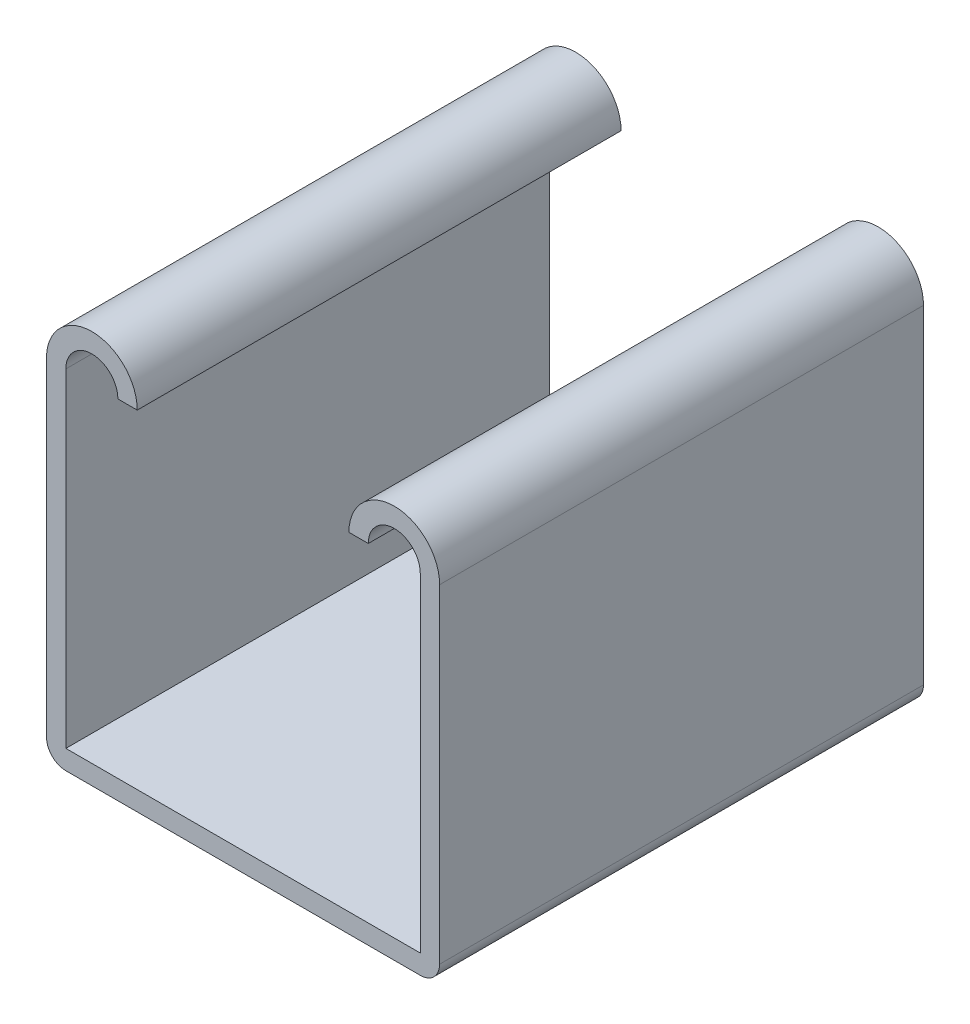
SolidWorks part; units mm, degrees
ref_plane "Plane1" through (0, 0, 0) normal (0, 0, 1) x (1, 0, 0)
ref_plane "Plane2" through (0, 0, 0) normal (0, 1, 0) x (1, 0, 0)
ref_plane "Plane3" through (0, 0, 0) normal (1, 0, 0) x (0, 0, -1)
sketch "Sketch1" plane through (0, 0, 0) normal (0, 0, 1) x (1, 0, 0)
  line L0 (-10.3188, 9.3789) -> (-10.3187, -7.874)
  line L1 (-9.3027, -8.89) -> (9.3028, -8.89)
  line L2 (10.3187, -7.874) -> (10.3187, 9.3789)
  line L3 (-6.5723, 9.3789) -> (-5.5562, 9.3789)
  line L4 (5.5562, 9.3789) -> (6.5722, 9.3789)
  line L6 (-9.3027, 9.3789) -> (-9.3027, -7.874)
  line L7 (-9.3027, -7.874) -> (9.3028, -7.874)
  line L8 (9.3028, -7.874) -> (9.3028, 9.3789)
  line L10 (-25.4, 11.7602) -> (25.4, 11.7602) construction
  arc A0 (10.3187, 9.3789) -> (5.5562, 9.3789) centre (7.9375, 9.3789) ccw
  arc A1 (-10.3188, 9.3789) -> (-5.5562, 9.3789) centre (-7.9375, 9.3789) cw
  arc A2 (-9.3027, -8.89) -> (-10.3187, -7.874) centre (-9.3027, -7.874) cw
  arc A3 (9.3028, -8.89) -> (10.3187, -7.874) centre (9.3028, -7.874) ccw
  arc A4 (-9.3027, 9.3789) -> (-6.5723, 9.3789) centre (-7.9375, 9.3789) cw
  arc A5 (9.3028, 9.3789) -> (6.5722, 9.3789) centre (7.9375, 9.3789) ccw
  dimension "D1" = 1.016
  dimension "D3" = 10.3187
  dimension "Width" = 20.6375
  dimension "D5" = 8.89
  dimension "D8" = 11.7602
  dimension "D2" = 2.3812
  dimension "D4" = 11.1125
  dimension "D6" = 4.7625
  dimension "D7" = 1.016
  dimension "gauge" = 1.016
extrude "Base-Extrude" add sketch "Sketch1" along normal mid plane 25.4
equation "\"D3@Sketch1\" = \"Width@Sketch1\" / 2"
equation "\"D1@Sketch1\" = \"gauge@Sketch1\""
